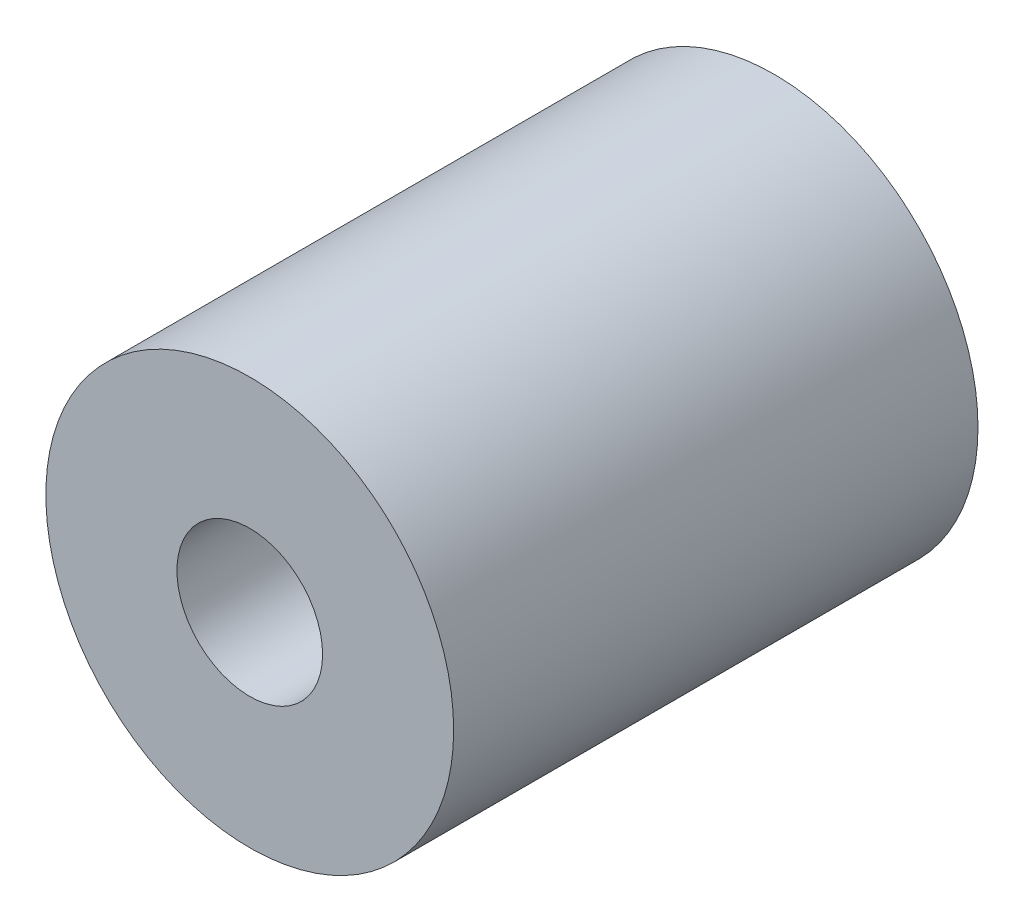
SolidWorks part; units mm, degrees
ref_plane "Front" through (0, 0, 0) normal (0, 0, 1) x (1, 0, 0)
ref_plane "Top" through (0, 0, 0) normal (0, 1, 0) x (1, 0, 0)
ref_plane "Right" through (0, 0, 0) normal (1, 0, 0) x (0, 0, -1)
sketch "Эскиз1" plane through (0, 0, 0) normal (0, 0, 1) x (1, 0, 0)
  line L1 (2.2805, -3.95) -> (4.5611, 0)
  line L2 (4.5611, 0) -> (2.2805, 3.95)
  line L3 (2.2805, 3.95) -> (-2.2805, 3.95)
  line L4 (-2.2805, 3.95) -> (-4.5611, 0)
  line L5 (-4.5611, 0) -> (-2.2805, -3.95)
  line L6 (-2.2805, -3.95) -> (2.2805, -3.95)
  circle A0 centre (0, 0) radius 3.95 construction
  circle A1 centre (0, 0) radius 7
  dimension "D2" = 14
  dimension "D1" = 7.9
extrude "Бобышка-Вытянуть1" add sketch "Эскиз1" along normal blind 8
sketch "Эскиз2" plane through (0, 0, 8) normal (0, 0, 1) x (1, 0, 0)
  circle A0 centre (0, 0) radius 2.5
  circle A1 centre (0, 0) radius 7
  dimension "D1" = 14
  dimension "D2" = 5
extrude "Бобышка-Вытянуть2" add sketch "Эскиз2" along normal blind 10
